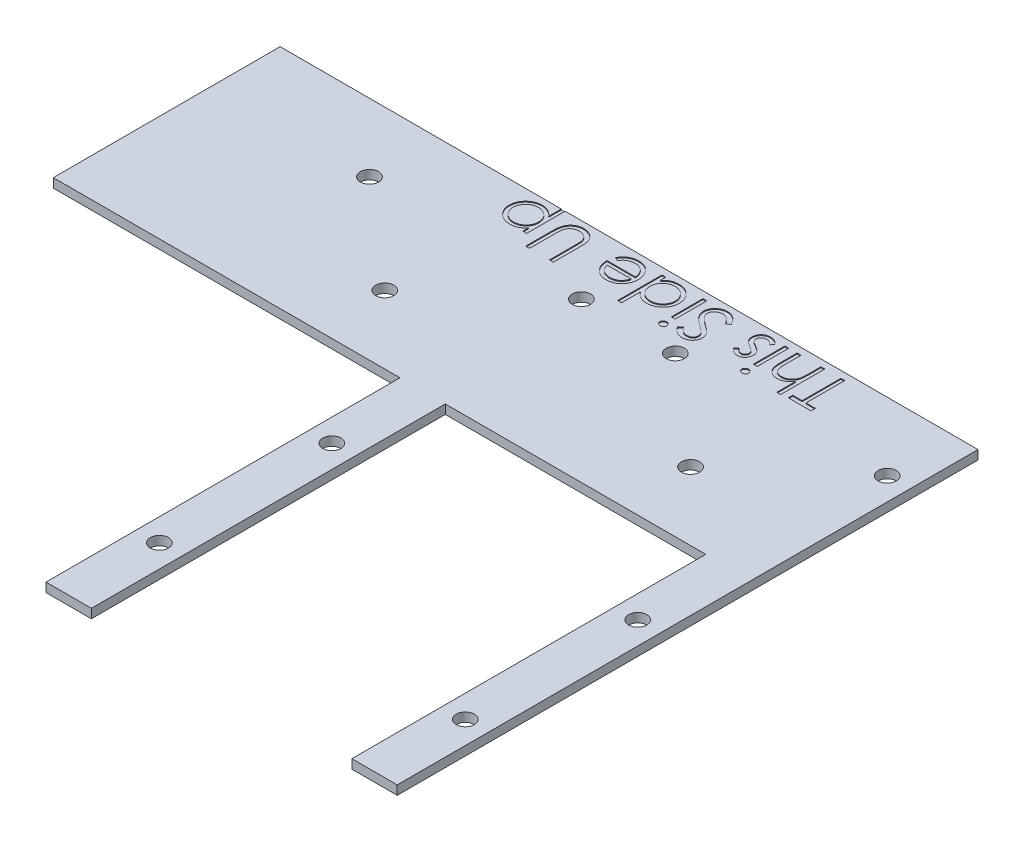
SolidWorks part; units mm, degrees
ref_plane "Front Plane" through (0, 0, 0) normal (0, 0, 1) x (1, 0, 0)
ref_plane "Top Plane" through (0, 0, 0) normal (0, 1, 0) x (1, 0, 0)
ref_plane "Right Plane" through (0, 0, 0) normal (1, 0, 0) x (0, 0, -1)
sketch "Sketch1" plane through (0, 0, 0) normal (0, 1, 0) x (1, 0, 0)
  line L0 (39.05, 25) -> (95.75, 25)
  line L1 (-28.35, 25) -> (28.35, 25)
  line L2 (-28.35, 25) -> (-28.35, -25)
  line L3 (-28.35, -25) -> (28.35, -25)
  line L4 (28.35, 25) -> (28.35, -25)
  line L5 (-28.35, 25) -> (28.35, -25) construction
  line L6 (-28.35, -25) -> (28.35, 25) construction
  line L7 (28.35, 25) -> (37.05, 25)
  line L8 (28.35, 25) -> (28.35, -25)
  line L9 (28.35, -25) -> (37.05, -25)
  line L10 (37.05, 25) -> (37.05, -25)
  line L11 (37.05, 25) -> (39.05, 25)
  line L12 (37.05, 25) -> (37.05, -25)
  line L13 (37.05, -25) -> (39.05, -25)
  line L14 (39.05, 25) -> (39.05, -25)
  line L15 (39.05, 25) -> (39.05, -25)
  line L16 (39.05, -25) -> (95.75, -25)
  line L17 (95.75, 25) -> (95.75, -25)
  line L19 (-28.35, -25) -> (-58.05, -25)
  line L20 (-28.35, -25) -> (-28.35, 25)
  line L21 (-28.35, 25) -> (-58.05, 25)
  line L22 (-58.05, -25) -> (-58.05, 25)
  line L23 (28.35, -25) -> (18.35, -25)
  line L24 (28.35, -25) -> (28.35, -103)
  line L25 (28.35, -103) -> (18.35, -103)
  line L26 (18.35, -25) -> (18.35, -103)
  line L27 (95.75, -25) -> (85.75, -25)
  line L28 (95.75, -25) -> (95.75, -103)
  line L29 (95.75, -103) -> (85.75, -103)
  line L30 (85.75, -25) -> (85.75, -103)
  circle A0 centre (-23.35, 10) radius 2
  circle A1 centre (0, -10) radius 2
  circle A2 centre (23.35, 10) radius 2
  circle A3 centre (44.05, 10) radius 2
  circle A4 centre (67.4, -10) radius 2
  circle A5 centre (90.75, 10) radius 2
  circle A6 centre (23.35, -45) radius 2
  circle A7 centre (23.35, -83) radius 2
  circle A8 centre (90.75, -45) radius 2
  circle A9 centre (90.75, -83) radius 2
  point P0 (0, 0)
  point P40 (90.75, -103)
  dimension "D2" = 4
  dimension "D3" = 4
  dimension "D4" = 4
  dimension "D5" = 15
  dimension "D6" = 15
  dimension "D14" = 4
  dimension "D15" = 4
  dimension "D16" = 4
  dimension "D17" = 5
  dimension "D18" = 5
  dimension "D19" = 28.35
  dimension "D20" = 35
  dimension "D23" = 15
  dimension "D24" = 15
  dimension "D25" = 29.7
  dimension "D26" = 10
  dimension "D28" = 4
  dimension "D29" = 4
  dimension "D30" = 5
  dimension "D31" = 5
  dimension "D34" = 4
  dimension "D35" = 4
  dimension "D39" = 20
  dimension "D1" = 50
  dimension "D7" = 35
  dimension "D8" = 56.7
  dimension "D9" = 5
  dimension "D10" = 5
  dimension "D11" = 28.35
  dimension "D12" = 50
  dimension "D13" = 56.7
  dimension "D21" = 2
  dimension "D22" = 8.7
  dimension "D27" = 128
  dimension "D32" = 10
  dimension "D33" = 128
  dimension "D36" = 20
  dimension "D37" = 20
  dimension "D38" = 20
extrude "Boss-Extrude1" add sketch "Sketch1" along normal blind 2 contours L4 L1 L2 L3 A2 A1 A0 | L10 L7 L4 L9 | L17 L0 L14 L16 A5 A4 A3 | L14 L11 L10 L13 | L22 L19 L2 L21 | L3 L26 L25 L24 | L16 L30 L29 L28 A9 A8
sketch "Sketch2" plane through (0, 2, 0) normal (0, 1, 0) x (1, 0, 0)
  line L0 (-3.3, 23.5) -> (70.7, 23.5) construction
  line L1 (-58.05, 25) -> (95.75, 25) construction
  line L2 (95.75, 25) -> (95.75, -103) construction
  line L3 (-28.35, 25) -> (-28.35, -25) construction
  text T0 "This Side Up" font "Century Gothic" height in points 36
  dimension "D1" = 1.5
  dimension "D2" = 74
  dimension "D3" = 25.05
  dimension "D4" = 25.05
extrude "Cut-Extrude1" cut sketch "Sketch2" against normal blind 0.2
